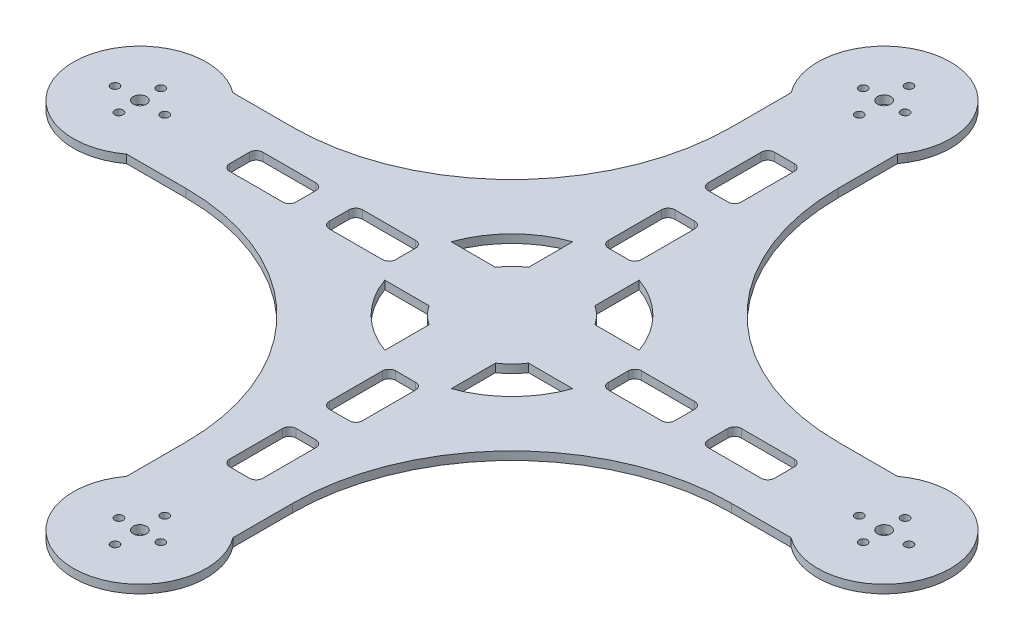
SolidWorks part; units mm, degrees
material "Acrylic (Medium-high impact)"
ref_plane "Front Plane" through (0, 0, 0) normal (0, 0, 1) x (1, 0, 0)
ref_plane "Top Plane" through (0, 0, 0) normal (0, 1, 0) x (1, 0, 0)
ref_plane "Right Plane" through (0, 0, 0) normal (1, 0, 0) x (0, 0, -1)
sketch "Sketch1" plane through (0, 0, 0) normal (0, 1, 0) x (1, 0, 0)
  line L0 (91.1016, -2.5359) -> (169.8416, -2.5359) construction
  line L1 (106.3416, 17.7841) -> (169.8416, 17.7841)
  line L2 (129.2016, -2.5359) -> (154.6016, -2.5359) construction
  line L3 (106.3416, -22.8559) -> (169.8416, -22.8559)
  line L4 (169.8416, 17.7841) -> (169.8416, -22.8559)
  line L5 (131.7416, 3.8141) -> (152.0616, 3.8141)
  line L6 (129.2016, 1.2741) -> (129.2016, -6.3459)
  line L7 (131.7416, -8.8859) -> (152.0616, -8.8859)
  line L8 (154.6016, 1.2741) -> (154.6016, -6.3459)
  line L9 (169.8416, 3.8141) -> (190.1616, 3.8141)
  line L10 (192.7016, 1.2741) -> (192.7016, -6.3459)
  line L11 (169.8416, -8.8859) -> (190.1616, -8.8859)
  line L12 (167.3016, 1.2741) -> (167.3016, -6.3459)
  line L21 (233.3416, 60.9641) -> (233.3416, -66.0359) construction
  line L22 (169.8416, -2.5359) -> (296.8416, -2.5359) construction
  line L23 (188.4403, -47.4372) -> (278.2428, 42.3654) construction
  line L24 (188.4403, 42.3654) -> (278.2428, -47.4372) construction
  line L25 (91.1016, 6.9641) -> (91.1016, -12.0359) construction
  line L26 (81.6016, -2.5359) -> (100.6016, -2.5359) construction
  line L27 (233.3416, -154.2759) -> (233.3416, -135.2759) construction
  line L28 (242.8416, -144.7759) -> (223.8416, -144.7759) construction
  line L29 (233.3416, -106.6759) -> (233.3416, -81.2759) construction
  line L30 (233.3416, -144.7759) -> (233.3416, -66.0359) construction
  line L39 (237.1516, -68.5759) -> (229.5316, -68.5759)
  line L40 (226.9916, -66.0359) -> (226.9916, -45.7159)
  line L41 (237.1516, -43.1759) -> (229.5316, -43.1759)
  line L42 (239.6916, -66.0359) -> (239.6916, -45.7159)
  line L43 (237.1516, -81.2759) -> (229.5316, -81.2759)
  line L44 (226.9916, -104.1359) -> (226.9916, -83.8159)
  line L45 (237.1516, -106.6759) -> (229.5316, -106.6759)
  line L46 (239.6916, -104.1359) -> (239.6916, -83.8159)
  line L47 (253.6616, -66.0359) -> (213.0216, -66.0359)
  line L48 (213.0216, -129.5359) -> (213.0216, -66.0359)
  line L49 (253.6616, -129.5359) -> (253.6616, -66.0359)
  line L50 (375.5816, -2.5359) -> (296.8416, -2.5359) construction
  line L51 (337.4816, -2.5359) -> (312.0816, -2.5359) construction
  line L52 (375.5816, -12.0359) -> (375.5816, 6.9641) construction
  line L53 (385.0816, -2.5359) -> (366.0816, -2.5359) construction
  line L54 (360.3416, -22.8559) -> (296.8416, -22.8559)
  line L55 (360.3416, 17.7841) -> (296.8416, 17.7841)
  line L56 (296.8416, -22.8559) -> (296.8416, 17.7841)
  line L57 (334.9416, -8.8859) -> (314.6216, -8.8859)
  line L58 (337.4816, -6.3459) -> (337.4816, 1.2741)
  line L59 (334.9416, 3.8141) -> (314.6216, 3.8141)
  line L60 (312.0816, -6.3459) -> (312.0816, 1.2741)
  line L61 (296.8416, -8.8859) -> (276.5216, -8.8859)
  line L62 (273.9816, -6.3459) -> (273.9816, 1.2741)
  line L63 (296.8416, 3.8141) -> (276.5216, 3.8141)
  line L64 (299.3816, -6.3459) -> (299.3816, 1.2741)
  line L73 (233.3416, 149.2041) -> (233.3416, 130.2041) construction
  line L74 (223.8416, 139.7041) -> (242.8416, 139.7041) construction
  line L75 (233.3416, 101.6041) -> (233.3416, 76.2041) construction
  line L76 (233.3416, 139.7041) -> (233.3416, 60.9641) construction
  line L85 (229.5316, 63.5041) -> (237.1516, 63.5041)
  line L86 (239.6916, 60.9641) -> (239.6916, 40.6441)
  line L87 (229.5316, 38.1041) -> (237.1516, 38.1041)
  line L88 (226.9916, 60.9641) -> (226.9916, 40.6441)
  line L89 (229.5316, 76.2041) -> (237.1516, 76.2041)
  line L90 (239.6916, 99.0641) -> (239.6916, 78.7441)
  line L91 (229.5316, 101.6041) -> (237.1516, 101.6041)
  line L92 (226.9916, 99.0641) -> (226.9916, 78.7441)
  line L93 (213.0216, 60.9641) -> (253.6616, 60.9641)
  line L94 (253.6616, 124.4641) -> (253.6616, 60.9641)
  line L95 (213.0216, 124.4641) -> (213.0216, 60.9641)
  line L96 (246.0416, -38.4569) -> (246.0416, -21.5435)
  line L97 (197.4205, 10.1641) -> (214.3339, 10.1641)
  line L99 (197.4205, -15.2359) -> (214.3339, -15.2359)
  line L100 (214.3339, 10.1641) -> (214.3339, -15.2359)
  line L101 (246.0416, -21.5435) -> (220.6416, -21.5435)
  line L102 (220.6416, -38.4569) -> (220.6416, -21.5435)
  line L105 (269.2626, -15.2359) -> (252.3492, -15.2359)
  line L106 (252.3492, -15.2359) -> (252.3492, 10.1641)
  line L107 (269.2626, 10.1641) -> (252.3492, 10.1641)
  line L108 (220.6416, 16.4717) -> (246.0416, 16.4717)
  line L109 (246.0416, 33.3852) -> (246.0416, 16.4717)
  line L111 (220.6416, 33.3852) -> (220.6416, 16.4717)
  circle A0 centre (91.1016, -2.5359) radius 25.4
  circle A1 centre (233.3416, -144.7759) radius 14 construction
  arc A2 (131.7416, -8.8859) -> (129.2016, -6.3459) centre (131.7416, -6.3459) cw
  arc A3 (154.6016, -6.3459) -> (152.0616, -8.8859) centre (152.0616, -6.3459) cw
  arc A4 (154.6016, 1.2741) -> (152.0616, 3.8141) centre (152.0616, 1.2741) ccw
  arc A5 (131.7416, 3.8141) -> (129.2016, 1.2741) centre (131.7416, 1.2741) ccw
  arc A6 (169.8416, 3.8141) -> (167.3016, 1.2741) centre (169.8416, 1.2741) ccw
  arc A7 (192.7016, 1.2741) -> (190.1616, 3.8141) centre (190.1616, 1.2741) ccw
  arc A8 (192.7016, -6.3459) -> (190.1616, -8.8859) centre (190.1616, -6.3459) cw
  arc A9 (169.8416, -8.8859) -> (167.3016, -6.3459) centre (169.8416, -6.3459) cw
  circle A10 centre (233.3416, -154.2759) radius 1.5875
  circle A11 centre (225.3416, -144.7759) radius 1.5875
  circle A12 centre (233.3416, -135.2759) radius 1.5875
  circle A13 centre (241.3416, -144.7759) radius 1.5875
  circle A14 centre (375.5816, 5.4641) radius 1.5875
  circle A15 centre (366.0816, -2.5359) radius 1.5875
  circle A16 centre (375.5816, -10.5359) radius 1.5875
  circle A17 centre (385.0816, -2.5359) radius 1.5875
  circle A18 centre (233.3416, -2.5359) radius 63.5
  circle A19 centre (91.1016, -2.5359) radius 8 construction
  circle A20 centre (91.1016, -2.5359) radius 9.5 construction
  circle A21 centre (91.1016, -2.5359) radius 14 construction
  circle A22 centre (233.3416, -144.7759) radius 9.5 construction
  circle A23 centre (233.3416, -144.7759) radius 8 construction
  circle A24 centre (233.3416, 149.2041) radius 1.5875
  circle A25 centre (241.3416, 139.7041) radius 1.5875
  circle A26 centre (233.3416, 130.2041) radius 1.5875
  circle A27 centre (225.3416, 139.7041) radius 1.5875
  circle A28 centre (91.1016, -2.5359) radius 2.54
  circle A29 centre (375.5816, -2.5359) radius 2.54
  circle A30 centre (233.3416, 139.7041) radius 2.54
  circle A31 centre (233.3416, -144.7759) radius 2.54
  arc A32 (226.9916, -66.0359) -> (229.5316, -68.5759) centre (229.5316, -66.0359) ccw
  arc A33 (229.5316, -43.1759) -> (226.9916, -45.7159) centre (229.5316, -45.7159) ccw
  arc A34 (237.1516, -43.1759) -> (239.6916, -45.7159) centre (237.1516, -45.7159) cw
  arc A35 (239.6916, -66.0359) -> (237.1516, -68.5759) centre (237.1516, -66.0359) cw
  arc A36 (239.6916, -104.1359) -> (237.1516, -106.6759) centre (237.1516, -104.1359) cw
  arc A37 (237.1516, -81.2759) -> (239.6916, -83.8159) centre (237.1516, -83.8159) cw
  arc A38 (229.5316, -81.2759) -> (226.9916, -83.8159) centre (229.5316, -83.8159) ccw
  arc A39 (226.9916, -104.1359) -> (229.5316, -106.6759) centre (229.5316, -104.1359) ccw
  circle A40 centre (233.3416, -144.7759) radius 25.4
  circle A41 centre (375.5816, -2.5359) radius 8 construction
  circle A42 centre (375.5816, -2.5359) radius 9.5 construction
  circle A43 centre (375.5816, -2.5359) radius 14 construction
  circle A44 centre (375.5816, -2.5359) radius 25.4
  arc A45 (334.9416, 3.8141) -> (337.4816, 1.2741) centre (334.9416, 1.2741) cw
  arc A46 (312.0816, 1.2741) -> (314.6216, 3.8141) centre (314.6216, 1.2741) cw
  arc A47 (312.0816, -6.3459) -> (314.6216, -8.8859) centre (314.6216, -6.3459) ccw
  arc A48 (334.9416, -8.8859) -> (337.4816, -6.3459) centre (334.9416, -6.3459) ccw
  arc A49 (296.8416, -8.8859) -> (299.3816, -6.3459) centre (296.8416, -6.3459) ccw
  arc A50 (273.9816, -6.3459) -> (276.5216, -8.8859) centre (276.5216, -6.3459) ccw
  arc A51 (273.9816, 1.2741) -> (276.5216, 3.8141) centre (276.5216, 1.2741) cw
  arc A52 (296.8416, 3.8141) -> (299.3816, 1.2741) centre (296.8416, 1.2741) cw
  circle A61 centre (233.3416, 139.7041) radius 14 construction
  circle A62 centre (233.3416, 139.7041) radius 9.5 construction
  circle A63 centre (233.3416, 139.7041) radius 8 construction
  arc A72 (239.6916, 60.9641) -> (237.1516, 63.5041) centre (237.1516, 60.9641) ccw
  arc A73 (237.1516, 38.1041) -> (239.6916, 40.6441) centre (237.1516, 40.6441) ccw
  arc A74 (229.5316, 38.1041) -> (226.9916, 40.6441) centre (229.5316, 40.6441) cw
  arc A75 (226.9916, 60.9641) -> (229.5316, 63.5041) centre (229.5316, 60.9641) cw
  arc A76 (226.9916, 99.0641) -> (229.5316, 101.6041) centre (229.5316, 99.0641) cw
  arc A77 (229.5316, 76.2041) -> (226.9916, 78.7441) centre (229.5316, 78.7441) cw
  arc A78 (237.1516, 76.2041) -> (239.6916, 78.7441) centre (237.1516, 78.7441) ccw
  arc A79 (239.6916, 99.0641) -> (237.1516, 101.6041) centre (237.1516, 99.0641) ccw
  circle A80 centre (233.3416, 139.7041) radius 25.4
  arc A81 (129.0958, 17.7841) -> (213.0216, 101.7099) centre (129.0958, 101.7099) ccw
  arc A82 (253.6616, -106.7816) -> (337.5873, -22.8559) centre (337.5873, -106.7816) cw
  arc A83 (253.6616, 101.7099) -> (337.5873, 17.7841) centre (337.5873, 101.7099) ccw
  arc A84 (129.0958, -22.8559) -> (213.0216, -106.7816) centre (129.0958, -106.7816) cw
  arc A85 (197.4205, -15.2359) -> (195.2416, -2.5359) centre (233.3416, -2.5359) ccw
  arc A87 (214.3339, -15.2359) -> (220.6416, -21.5435) centre (233.3416, -2.5359) ccw
  arc A88 (220.6416, 16.4717) -> (214.3339, 10.1641) centre (233.3416, -2.5359) ccw
  arc A89 (252.3492, 10.1641) -> (246.0416, 16.4717) centre (233.3416, -2.5359) ccw
  arc A90 (246.0416, -21.5435) -> (252.3492, -15.2359) centre (233.3416, -2.5359) ccw
  circle A91 centre (233.3416, -2.5359) radius 38.1
  circle A92 centre (91.1016, -10.5359) radius 1.5875
  circle A93 centre (91.1016, 5.4641) radius 1.5875
  circle A94 centre (81.6016, -2.5359) radius 1.5875
  circle A95 centre (100.6016, -2.5359) radius 1.5875
  point P19 (129.0958, 17.7841)
  point P23 (116.5016, -2.5359)
  point P75 (91.1016, 5.4641)
  point P76 (91.1016, -10.5359)
  point P78 (81.6016, -2.5359)
  point P79 (100.6016, -2.5359)
  point P142 (225.3416, -144.7759)
  point P143 (241.3416, -144.7759)
  point P144 (233.3416, -119.3759)
  point P145 (213.0216, 101.7099)
  point P210 (350.1816, -2.5359)
  point P211 (375.5816, -10.5359)
  point P212 (375.5816, 5.4641)
  point P276 (241.3416, 139.7041)
  point P277 (225.3416, 139.7041)
  point P278 (233.3416, 114.3041)
  dimension "D1" = 50.8
  dimension "D2" = 38.1
  dimension "D3" = 2.54
  dimension "D6" = 12.7
  dimension "D9" = 127
  dimension "D12" = 16
  dimension "D13" = 19
  dimension "D14" = 28
  dimension "D10" = 45.72
  dimension "D15" = 3.175
  dimension "D17" = 38.1
  dimension "D18" = 5.08
  dimension "D19" = 5.08
  dimension "D4" = 12.7
  dimension "D5" = 25.4
  dimension "D7" = 40.64
  dimension "D8" = 2
  dimension "D11" = 25.4
  dimension "D16" = 63.5
extrude "Boss-Extrude1" add sketch "Sketch1" along normal blind 3.175 contours L94 A80 L95 L93 L88 A75 L85 A72 L86 A73 L87 A74 A79 L90 A78 L89 A77 L92 A76 L91 | A18 A91 A85 | A81 A18 L93 L95 | A81 L1 L4 A18 | A0 L3 L4 L1 A5 L5 A4 L8 A3 L7 A2 L6 L11 A9 L12 A6 L9 A7 L10 A8 | A0 A95 A94 A93 A92 | L3 A84 A18 L4 | A18 A84 L48 L47 | L48 A40 L49 L47 L42 A35 L39 A32 L40 A33 L41 A34 A39 L44 A38 L43 A37 L46 A36 L45 | A40 A13 A11 A10 A12 | L49 A82 A18 L47 | A18 A82 L54 L56 | A44 L55 L56 L54 A48 L57 A47 L60 A46 L59 A45 L58 L63 A52 L64 A49 L61 A50 L62 A51 | A83 A18 L56 L55 | A83 L94 L93 A18 | A44 A17 A16 A15 A14 | A80 A27 A25 A24 A26 | L101 A90 L106 A89 L108 A88 L100 A87 | L102 A85 L96 L101 | L105 A85 L107 L106 | A85 A91 L99 L100 L97 | L109 A85 L111 L108
ref_plane "Plane1" through (233.3416, 0, 0) normal (1, 0, 0) x (0, 0, -1)
ref_plane "Plane2" through (0, 0, 2.5359) normal (0, 0, 1) x (1, 0, 0)
sketch "Sketch5" plane through (0, 0, 0) normal (0, -1, 0) x (1, 0, 0)
  line L0 (220.6416, 46.9859) -> (246.0416, 46.9859) construction
  line L1 (233.3416, -6.6955) -> (233.3416, 6.6955) construction
  line L2 (277.7916, 15.2359) -> (277.7916, -10.1641) construction
  line L3 (303.1916, 15.2359) -> (303.1916, -10.1641) construction
  line L4 (246.0416, -41.9141) -> (220.6416, -41.9141) construction
  line L5 (246.0416, -67.3141) -> (220.6416, -67.3141) construction
  line L6 (163.4916, -10.1641) -> (163.4916, 15.2359) construction
  line L7 (188.8916, -10.1641) -> (188.8916, 15.2359) construction
  circle A0 centre (233.3416, 46.9859) radius 1.651
  circle A1 centre (233.3416, 72.3859) radius 1.651
  circle A2 centre (277.7916, 2.5359) radius 1.651
  circle A3 centre (303.1916, 2.5359) radius 1.651
  circle A4 centre (233.3416, -41.9141) radius 1.651
  circle A5 centre (233.3416, -67.3141) radius 1.651
  circle A6 centre (163.4916, 2.5359) radius 1.651
  circle A7 centre (188.8916, 2.5359) radius 1.651
equation "\"ARM_TOTAL_LENGTH\" = 2.5in"
equation "\"ARM_TOTAL_WIDTH\"= 1.6in"
equation "\"MOTOR_MOUNT_TOTAL_RADIUS\"= 1in"
equation "\"MOTOR_CAVITY_RADIUS\"= 1in"
equation "\"D1@Sketch1\"=\"MOTOR_MOUNT_TOTAL_RADIUS\" * 2"
equation "\"D7@Sketch1\"=\"ARM_TOTAL_WIDTH\""
equation "\"BODY_DIAMETER\"= 3in"
equation "\"MOTOR_DIAMETER\"= 28mm"
equation "\"D14@Sketch1\"=\"MOTOR_DIAMETER\""
equation "\"D16@Sketch1\"=\"ARM_TOTAL_LENGTH\""
equation "\"D2@Sketch1\"=\"BODY_DIAMETER\"/2"
